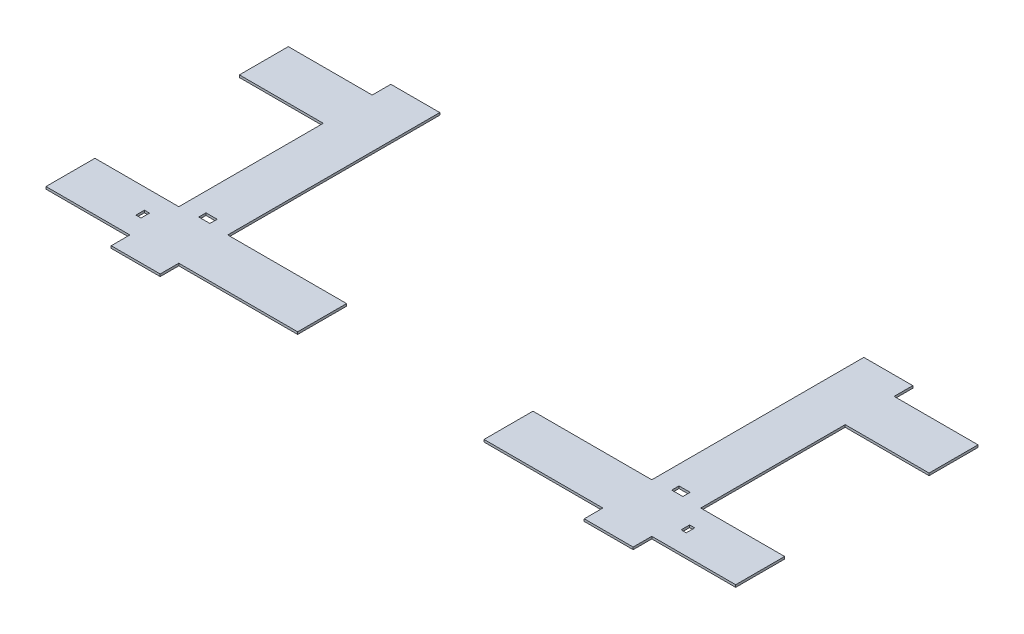
SolidWorks part; units mm, degrees
ref_plane "前视基准面" through (0, 0, 0) normal (0, 0, 1) x (1, 0, 0)
ref_plane "上视基准面" through (0, 0, 0) normal (0, 1, 0) x (1, 0, 0)
ref_plane "右视基准面" through (0, 0, 0) normal (1, 0, 0) x (0, 0, -1)
sketch "草图1" plane through (0, 0, 0) normal (0, 1, 0) x (1, 0, 0)
  line L0 (0, 0) -> (0, -8)
  line L1 (0, -8) -> (-21, -8)
  line L2 (-21, -8) -> (-21, 0)
  line L3 (-21, 0) -> (-57, 0)
  line L4 (-57, 0) -> (-57, 21)
  line L5 (-57, 21) -> (-21, 21)
  line L6 (-21, 21) -> (-21, 83)
  line L7 (-21, 112) -> (0, 112)
  line L8 (0, 112) -> (0, 21)
  line L9 (0, 21) -> (51, 21)
  line L10 (51, 21) -> (51, 0)
  line L11 (51, 0) -> (0, 0)
  line L12 (-21, 0) -> (0, 0) construction
  line L13 (0, 21) -> (0, 0) construction
  line L14 (-21, 31) -> (0, 31) construction
  line L15 (-21, 73) -> (0, 73) construction
  line L16 (-21, 104) -> (0, 104) construction
  line L17 (-49, 21) -> (-49, 0) construction
  line L18 (-21, 104) -> (-57, 104)
  line L19 (-57, 104) -> (-57, 83)
  line L20 (-57, 83) -> (-21, 83)
  line L21 (-49, 104) -> (-49, 83) construction
  line L22 (-21, 104) -> (-21, 112)
  line L23 (43, 21) -> (43, 0) construction
  line L24 (44, 21) -> (44, 0) construction
  line L25 (-50, 21) -> (-50, 0) construction
  line L26 (-21, -1) -> (0, -1) construction
  line L27 (-50, 104) -> (-50, 83) construction
  line L28 (-21, 105) -> (0, 105) construction
  line L29 (-21, 74) -> (0, 74) construction
  line L30 (-21, 30) -> (0, 30) construction
  line L31 (1, 21) -> (1, 0) construction
  line L32 (-86.1631, 10.5) -> (100.3958, 10.5) construction
  line L33 (-10.5, 125.5603) -> (-10.5, -39.8093) construction
  line L34 (-27.1012, 12.329) -> (-24.8988, 12.329)
  line L35 (-27.1012, 12.329) -> (-27.1012, 8.671)
  line L36 (-27.1012, 8.671) -> (-24.8988, 8.671)
  line L37 (-24.8988, 12.329) -> (-24.8988, 8.671)
  line L38 (-27.1012, 12.329) -> (-24.8988, 8.671) construction
  line L39 (-27.1012, 8.671) -> (-24.8988, 12.329) construction
  line L40 (91, 123.0084) -> (91, -28.4072) construction
  line L41 (-12.8928, 24.5605) -> (-8.1072, 24.5605)
  line L42 (-12.8928, 24.5605) -> (-12.8928, 21.4395)
  line L43 (-12.8928, 21.4395) -> (-8.1072, 21.4395)
  line L44 (-8.1072, 24.5605) -> (-8.1072, 21.4395)
  line L45 (-12.8928, 24.5605) -> (-8.1072, 21.4395) construction
  line L46 (-12.8928, 21.4395) -> (-8.1072, 24.5605) construction
  line L47 (194.8928, 21.4395) -> (190.1072, 24.5605) construction
  line L48 (194.8928, 24.5605) -> (190.1072, 21.4395) construction
  line L49 (209.1012, 8.671) -> (206.8988, 12.329) construction
  line L50 (209.1012, 12.329) -> (206.8988, 8.671) construction
  line L51 (192.5, 125.5603) -> (192.5, -39.8093) construction
  line L52 (268.1631, 10.5) -> (81.6042, 10.5) construction
  line L53 (181, 21) -> (181, 0) construction
  line L54 (203, 30) -> (182, 30) construction
  line L55 (203, 74) -> (182, 74) construction
  line L56 (203, 105) -> (182, 105) construction
  line L57 (232, 104) -> (232, 83) construction
  line L58 (203, -1) -> (182, -1) construction
  line L59 (232, 21) -> (232, 0) construction
  line L60 (138, 21) -> (138, 0) construction
  line L61 (139, 21) -> (139, 0) construction
  line L62 (231, 104) -> (231, 83) construction
  line L63 (231, 21) -> (231, 0) construction
  line L64 (203, 104) -> (182, 104) construction
  line L65 (203, 73) -> (182, 73) construction
  line L66 (203, 31) -> (182, 31) construction
  line L67 (182, 21) -> (182, 0) construction
  line L68 (203, 0) -> (182, 0) construction
  line L69 (190.1072, 24.5605) -> (190.1072, 21.4395)
  line L70 (194.8928, 21.4395) -> (190.1072, 21.4395)
  line L71 (194.8928, 24.5605) -> (194.8928, 21.4395)
  line L72 (194.8928, 24.5605) -> (190.1072, 24.5605)
  line L73 (206.8988, 12.329) -> (206.8988, 8.671)
  line L74 (209.1012, 8.671) -> (206.8988, 8.671)
  line L75 (209.1012, 12.329) -> (209.1012, 8.671)
  line L76 (209.1012, 12.329) -> (206.8988, 12.329)
  line L77 (203, 104) -> (203, 112)
  line L78 (239, 83) -> (203, 83)
  line L79 (239, 104) -> (239, 83)
  line L80 (203, 104) -> (239, 104)
  line L81 (131, 0) -> (182, 0)
  line L82 (131, 21) -> (131, 0)
  line L83 (182, 21) -> (131, 21)
  line L84 (182, 112) -> (182, 21)
  line L85 (203, 112) -> (182, 112)
  line L86 (203, 21) -> (203, 83)
  line L87 (239, 21) -> (203, 21)
  line L88 (239, 0) -> (239, 21)
  line L89 (203, 0) -> (239, 0)
  line L90 (203, -8) -> (203, 0)
  line L91 (182, -8) -> (203, -8)
  line L92 (182, 0) -> (182, -8)
  point P46 (-26, 10.5)
  point P53 (-10.5, 23)
  point P58 (10, 10.5)
  point P59 (-10.5, 41)
  point P117 (192.5, 41)
  point P118 (172, 10.5)
  point P119 (192.5, 23)
  point P120 (208, 10.5)
  dimension "D1" = 21
  dimension "D2" = 8
  dimension "D3" = 31
  dimension "D4" = 42
  dimension "D5" = 31
  dimension "D6" = 8
  dimension "D7" = 21
  dimension "D8" = 8
  dimension "D9" = 28
  dimension "D10" = 21
  dimension "D11" = 8
  dimension "D12" = 28
  dimension "D13" = 43
  dimension "D14" = 8
  dimension "D15" = 1
  dimension "D16" = 1
  dimension "D17" = 1
  dimension "D18" = 1
  dimension "D19" = 1
  dimension "D20" = 1
  dimension "D21" = 1
  dimension "D22" = 1
  dimension "D23" = 10.5
  dimension "D24" = 23
  dimension "D25" = 10.5
  dimension "D26" = 23
  dimension "D27" = 10
  dimension "D28" = 10
  dimension "D29" = 80
  dimension "D30" = 21
  dimension "D31" = 108
  dimension "D32" = 51
  dimension "D33" = 91
  dimension "D34" = 36
  dimension "D35" = 23
  dimension "D36" = 23
  dimension "D37" = 10
  dimension "D38" = 10
extrude "凸台-拉伸1" add sketch "草图1" along normal blind 1
